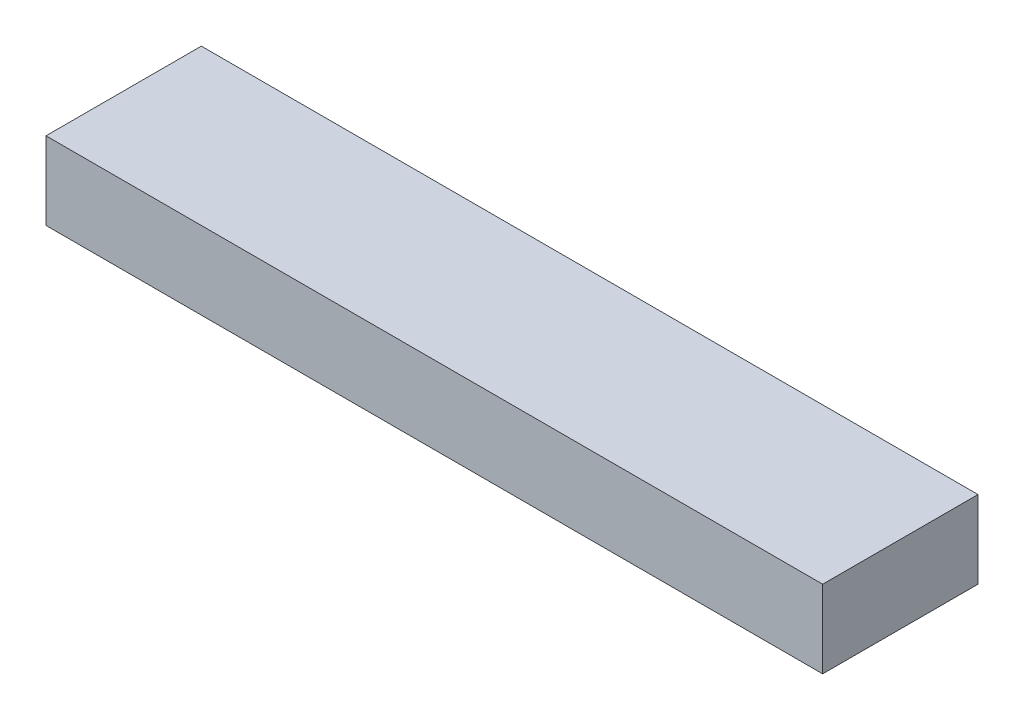
SolidWorks part; units mm, degrees
ref_plane "Front Plane" through (0, 0, 0) normal (0, 0, 1) x (1, 0, 0)
ref_plane "Top Plane" through (0, 0, 0) normal (0, 1, 0) x (1, 0, 0)
ref_plane "Right Plane" through (0, 0, 0) normal (1, 0, 0) x (0, 0, -1)
sketch "Sketch1" plane through (0, 0, 0) normal (0, 1, 0) x (1, 0, 0)
  line L1 (-63.5, -12.7) -> (63.5, -12.7)
  line L2 (-63.5, -12.7) -> (-63.5, 12.7)
  line L3 (-63.5, 12.7) -> (63.5, 12.7)
  line L4 (63.5, -12.7) -> (63.5, 12.7)
  line L5 (-63.5, -12.7) -> (63.5, 12.7) construction
  line L6 (-63.5, 12.7) -> (63.5, -12.7) construction
  point P0 (0, 0)
  dimension "D1" = 127
  dimension "D2" = 25.4
extrude "Boss-Extrude1" add sketch "Sketch1" along normal blind 12.7
